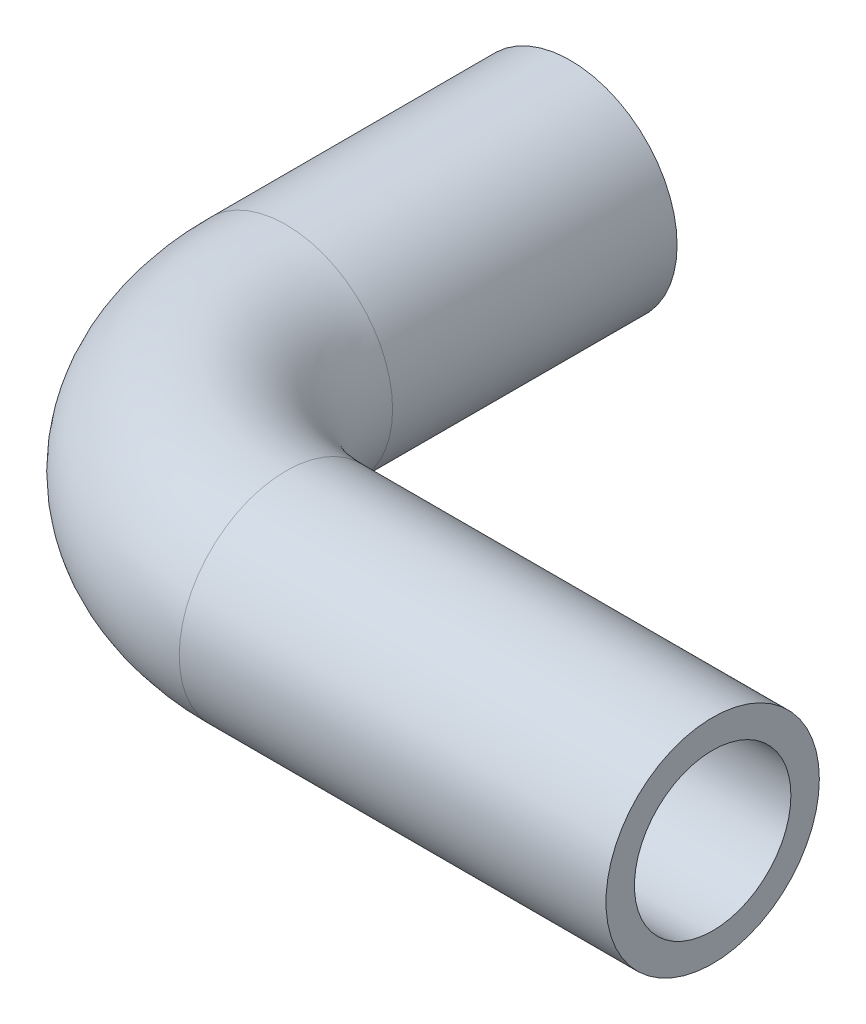
SolidWorks part; units mm, degrees
material "Plain Carbon Steel"
ref_plane "Front Plane" through (0, 0, 0) normal (0, 0, 1) x (1, 0, 0)
ref_plane "Top Plane" through (0, 0, 0) normal (0, 1, 0) x (1, 0, 0)
ref_plane "Right Plane" through (0, 0, 0) normal (1, 0, 0) x (0, 0, -1)
sketch "Sketch2" plane through (0, 0, 0) normal (0, 1, 0) x (1, 0, 0)
  line L0 (0, 0) -> (150, 0)
  line L1 (-75, 175) -> (-75, 75)
  arc A0 (-75, 75) -> (0, 0) centre (0, 75) ccw
  dimension "150" = 150
  dimension "D2" = 75
  dimension "D3" = 75
  dimension "D4" = 100
sketch "Sketch3" plane through (0, 0, 0) normal (1, 0, 0) x (0, 0, -1)
  circle A0 centre (0, 0) radius 37.5
  dimension "D1" = 75
sweep "Sweep1" add path "Sketch2" circular profile diameter 75 parameters "D3"=75
shell "Shell1" thickness 10
sketch "Sketch4" plane through (0, 0, -175) normal (0, 0, -1) x (-1, 0, 0)
  line L0 (75, 27.5) -> (75, 37.5)
  circle A0 centre (75, 0) radius 27.5
  circle A1 centre (75, 0) radius 37.5 construction
  dimension "D1" = 10
extrude "Cut-Extrude1" cut sketch "Sketch4" against normal up to next contours A0
